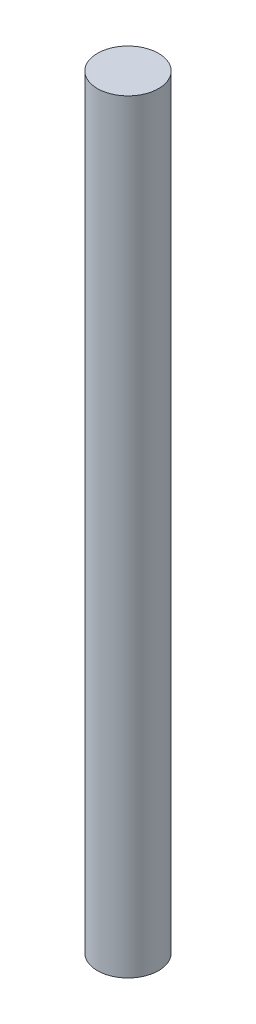
SolidWorks part; units mm, degrees
ref_plane "Front Plane" through (0, 0, 0) normal (0, 0, 1) x (1, 0, 0)
ref_plane "Top Plane" through (0, 0, 0) normal (0, 1, 0) x (1, 0, 0)
ref_plane "Right Plane" through (0, 0, 0) normal (1, 0, 0) x (0, 0, -1)
sketch "Sketch1" plane through (0, 0, 0) normal (0, 1, 0) x (1, 0, 0)
  circle A0 centre (0, 0) radius 2.54
extrude "Boss-Extrude1" add sketch "Sketch1" along normal blind 63.5
